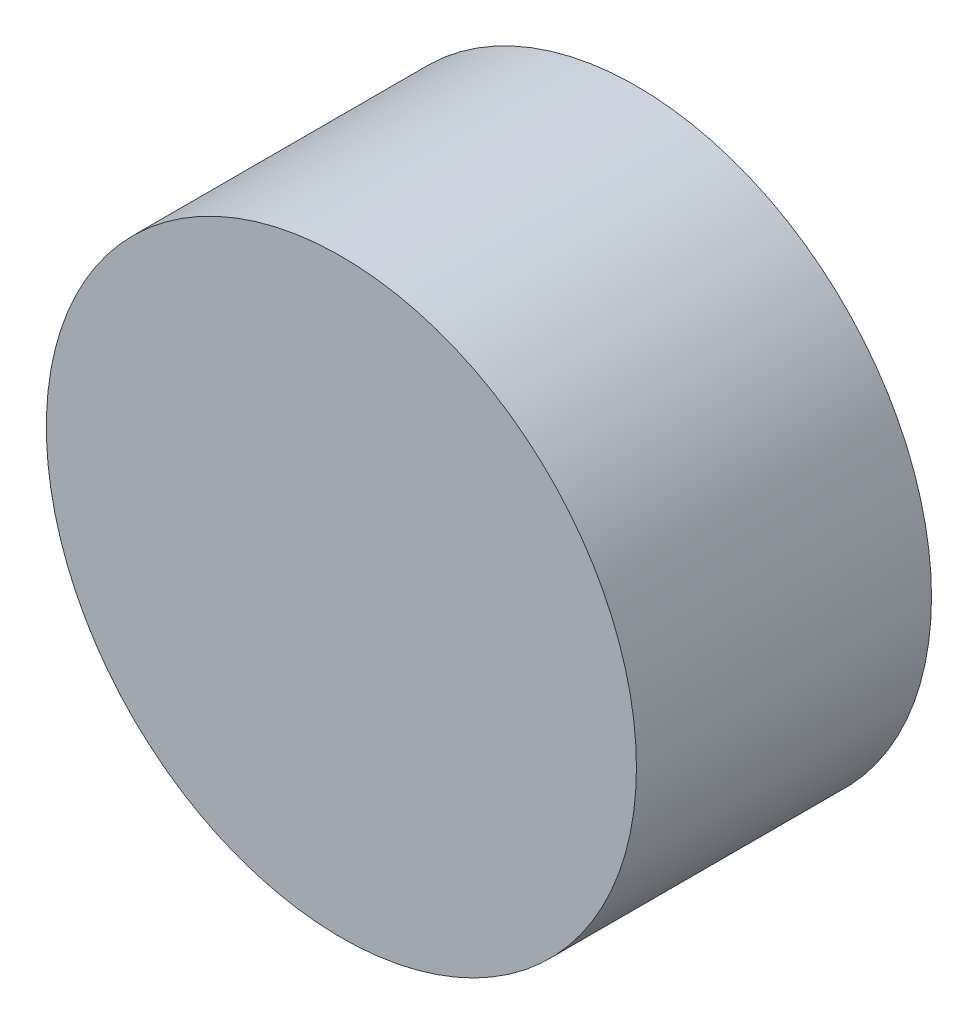
SolidWorks part; units mm, degrees
ref_plane "Front Plane" through (0, 0, 0) normal (0, 0, 1) x (1, 0, 0)
ref_plane "Top Plane" through (0, 0, 0) normal (0, 1, 0) x (1, 0, 0)
ref_plane "Right Plane" through (0, 0, 0) normal (1, 0, 0) x (0, 0, -1)
sketch "Sketch1" plane through (0, 0, 0) normal (0, 0, 1) x (1, 0, 0)
  circle A0 centre (0, 0) radius 1
  dimension "D1" = 2
extrude "Boss-Extrude1" add sketch "Sketch1" along normal mid plane 1
